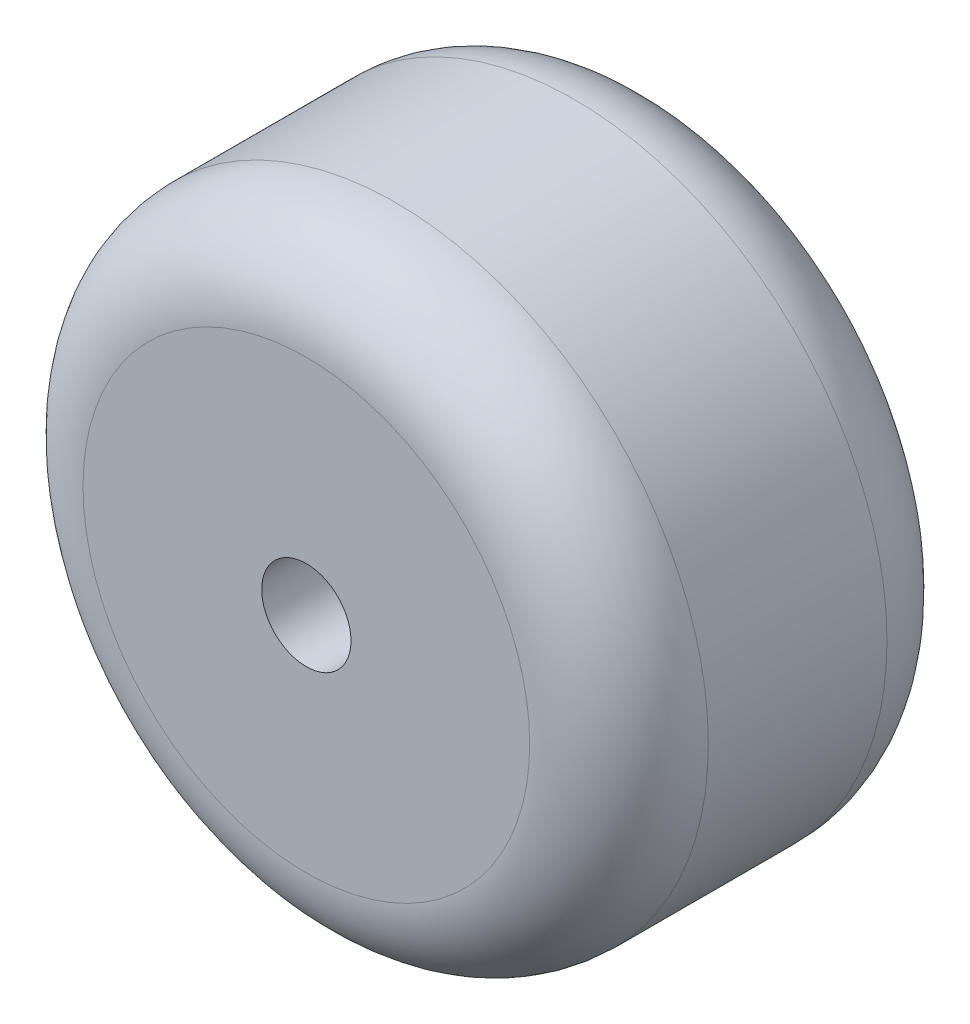
SolidWorks part; units mm, degrees
ref_plane "Front Plane" through (0, 0, 0) normal (0, 0, 1) x (1, 0, 0)
ref_plane "Top Plane" through (0, 0, 0) normal (0, 1, 0) x (1, 0, 0)
ref_plane "Right Plane" through (0, 0, 0) normal (1, 0, 0) x (0, 0, -1)
sketch "Sketch1" plane through (0, 0, 0) normal (0, 0, 1) x (1, 0, 0)
  circle A0 centre (0, 0) radius 35
extrude "Boss-Extrude1" add sketch "Sketch1" along normal blind 40 contours A0
fillet "Fillet1" radius 10 2 edges at (35, 0, 40) (35, 0, 0)
sketch "Sketch2" plane through (0, 0, 40) normal (0, 0, 1) x (1, 0, 0)
  circle A0 centre (0, 0) radius 5
extrude "Cut-Extrude1" cut sketch "Sketch2" against normal blind 40
